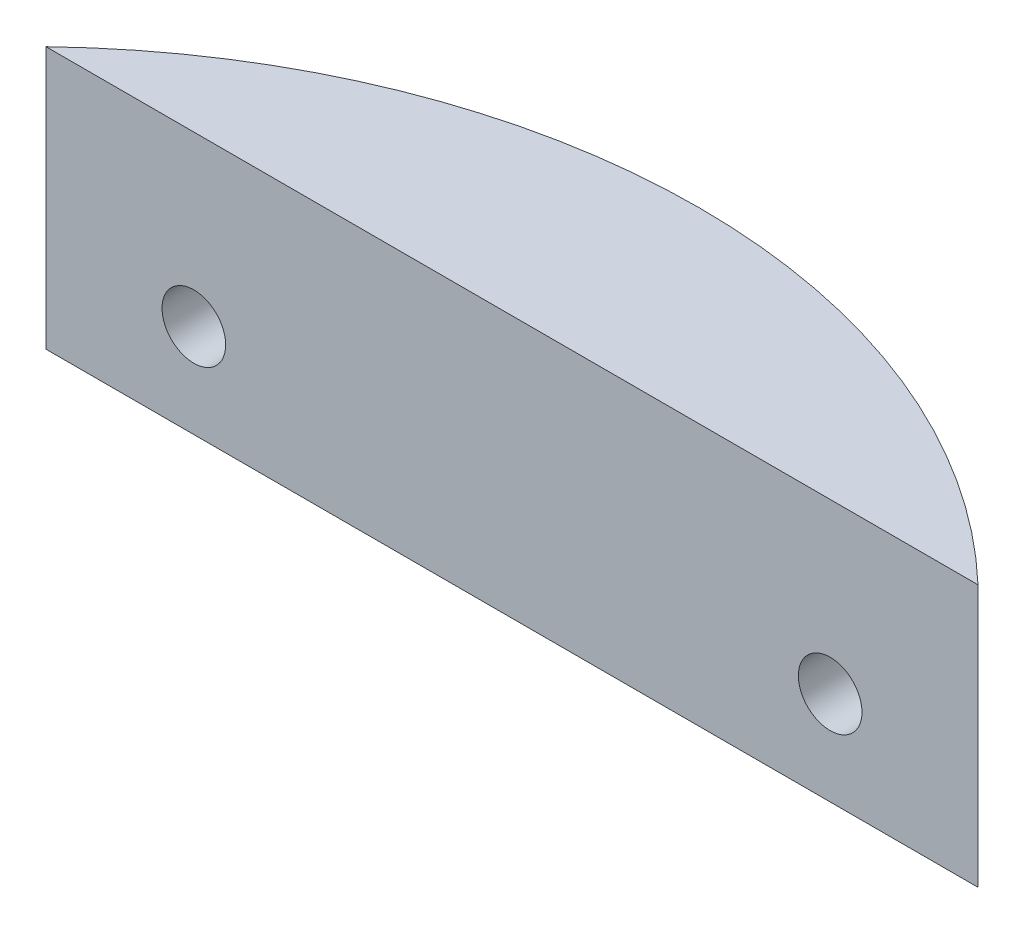
SolidWorks part; units mm, degrees
ref_plane "Front Plane" through (0, 0, 0) normal (0, 0, 1) x (1, 0, 0)
ref_plane "Top Plane" through (0, 0, 0) normal (0, 1, 0) x (1, 0, 0)
ref_plane "Right Plane" through (0, 0, 0) normal (1, 0, 0) x (0, 0, -1)
sketch "Sketch1" plane through (0, 0, 0) normal (0, 1, 0) x (1, 0, 0)
  line L0 (-62.2495, 65) -> (62.2495, 65)
  arc A0 (-62.2495, 65) -> (62.2495, 65) centre (0, 0) cw
  dimension "D1" = 65
  dimension "D2" = 90
extrude "Boss-Extrude1" add sketch "Sketch1" along normal blind 35
sketch "Sketch2" plane through (0, 0, -65) normal (0, 0, 1) x (1, 0, 0)
  line L0 (0, 52.8627) -> (0, -34.1258) construction
  line L2 (-62.2495, 35) -> (62.2495, 35) construction
  circle A0 centre (-42.5, 12.5) radius 4.25
  circle A1 centre (42.5, 12.5) radius 4.25
  dimension "D3" = 8.5
  dimension "D4" = 8.5
  dimension "D1" = 85
  dimension "D2" = 22.5
extrude "Cut-Extrude1" cut sketch "Sketch2" against normal blind 10
